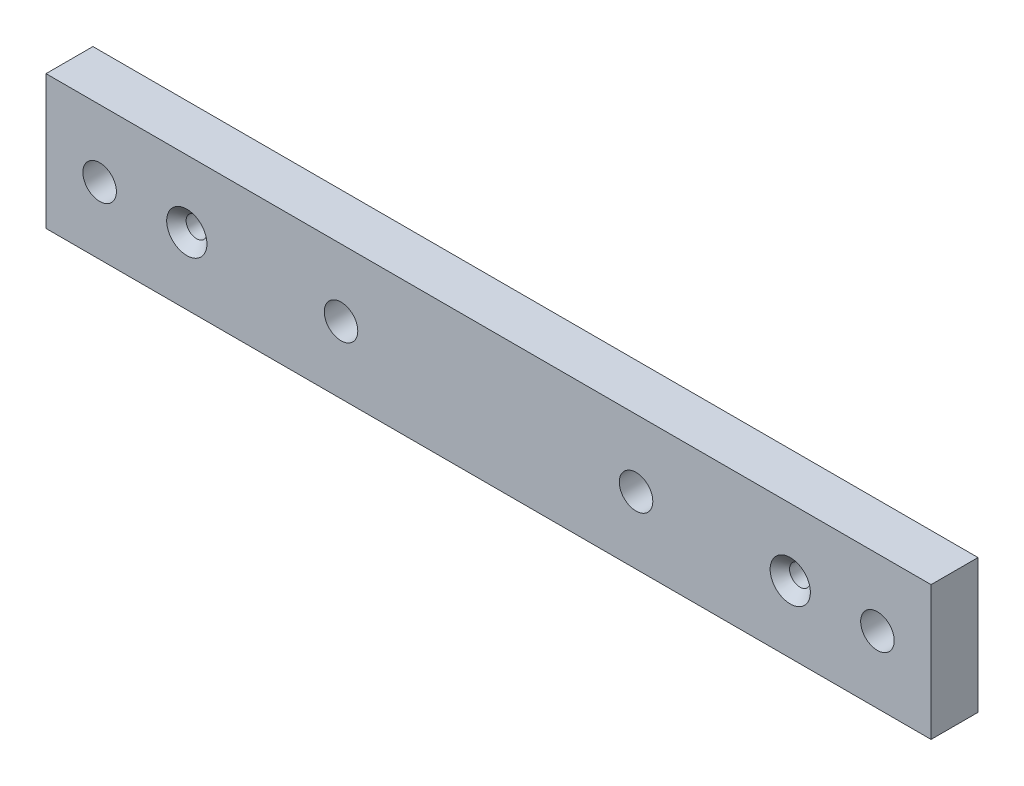
SolidWorks part; units mm, degrees
ref_plane "Front" through (0, 0, 0) normal (0, 0, 1) x (1, 0, 0)
ref_plane "Top" through (0, 0, 0) normal (0, 1, 0) x (1, 0, 0)
ref_plane "Right" through (0, 0, 0) normal (1, 0, 0) x (0, 0, -1)
sketch "Sketch1" plane through (0, 0, 0) normal (0, 0, 1) x (1, 0, 0)
  line L1 (-66, -10) -> (66, -10)
  line L2 (-66, -10) -> (-66, 10)
  line L3 (-66, 10) -> (66, 10)
  line L4 (66, -10) -> (66, 10)
  line L5 (-66, -10) -> (66, 10) construction
  line L6 (-66, 10) -> (66, -10) construction
  circle A0 centre (-45, 0) radius 1.5
  circle A1 centre (45, 0) radius 1.5
  circle A2 centre (-22, 0) radius 2.5
  circle A3 centre (22, 0) radius 2.5
  circle A4 centre (-58, 0) radius 2.5
  circle A5 centre (58, 0) radius 2.5
  point P0 (0, 0)
  point P18 (0, 0)
  dimension "D3" = 3
  dimension "D4" = 3
  dimension "D7" = 5
  dimension "D8" = 5
  dimension "D9" = 22
  dimension "D11" = 5
  dimension "D12" = 5
  dimension "D1" = 20
  dimension "D2" = 132
  dimension "D5" = 90
  dimension "D6" = 45
  dimension "D10" = 22
  dimension "D13" = 13
  dimension "D14" = 13
extrude "Boss-Extrude1" add sketch "Sketch1" along normal blind 7
hole_wizard "CSK for M4 Countersunk Flat Head Screw1" positions "3DSketch1" profile "Sketch2" countersink size "M4" standard "ISO" end condition through all
sketch3d "3DSketch1"
  line L0 (-45, 0, 7) -> (-45, 0, 0) construction
  line L1 (45, 0, 7) -> (45, 0, 0) construction
  point P0 (-45, 0, 7)
  point P4 (45, 0, 7)
sketch "Sketch2" plane through (-45, 0, 7) normal (1, 0, 0) x (0, -1, 0)
  line L0 (0, 0) -> (0, 7)
  line L1 (0, 7) -> (1.55, 7)
  line L2 (1.55, 7) -> (1.55, 1.45)
  line L3 (1.55, 1.45) -> (3, 0)
  line L5 (3, 0) -> (0, 0)
  line L6 (-1.55, 1.45) -> (-3, 0) construction
  line L11 (0, -6.35) -> (0, 107.95) construction
  dimension "Thru Hole Dia." = 3.1
  dimension "Thru Hole Depth" = 7
  dimension "Near C'Sink Dia." = 6
  dimension "Near C'Sink Angle" = 90
